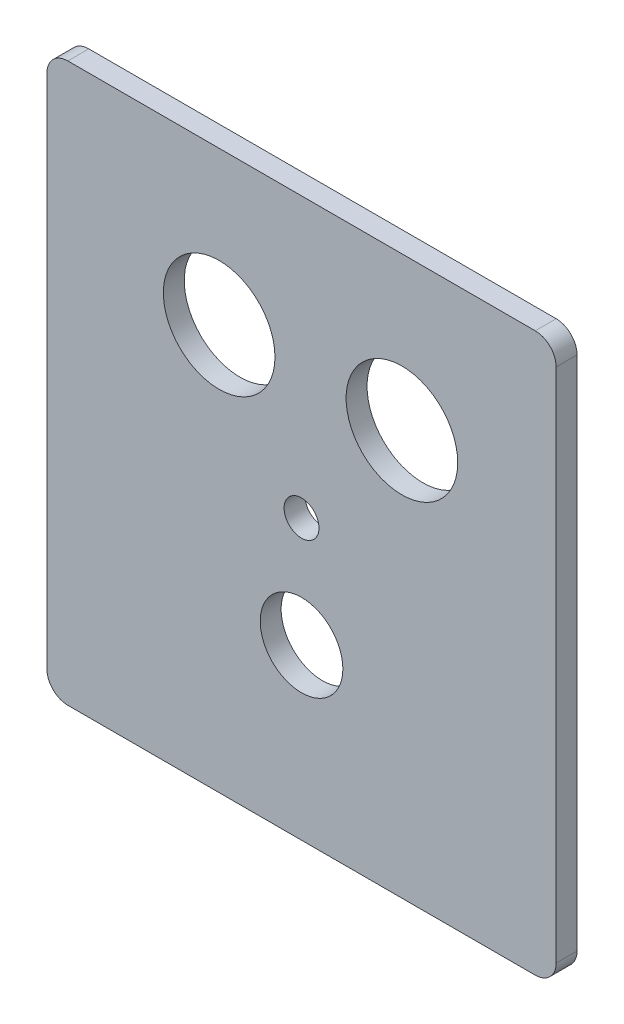
SolidWorks part; units mm, degrees
ref_plane "Front Plane" through (0, 0, 0) normal (0, 0, 1) x (1, 0, 0)
ref_plane "Top Plane" through (0, 0, 0) normal (0, 1, 0) x (1, 0, 0)
ref_plane "Right Plane" through (0, 0, 0) normal (1, 0, 0) x (0, 0, -1)
sketch "Sketch2" plane through (0, 0, 0) normal (0, 0, 1) x (1, 0, 0)
  line L1 (-105.9527, 11.6949) -> (-38.9527, 11.6949)
  line L2 (-108.9527, 8.6949) -> (-108.9527, -65.3051)
  line L3 (-105.9527, -68.3051) -> (-38.9527, -68.3051)
  line L4 (-35.9527, 8.6949) -> (-35.9527, -65.3051)
  arc A0 (-108.9527, -65.3051) -> (-105.9527, -68.3051) centre (-105.9527, -65.3051) ccw
  arc A1 (-38.9527, -68.3051) -> (-35.9527, -65.3051) centre (-38.9527, -65.3051) ccw
  arc A2 (-38.9527, 11.6949) -> (-35.9527, 8.6949) centre (-38.9527, 8.6949) cw
  arc A3 (-105.9527, 11.6949) -> (-108.9527, 8.6949) centre (-105.9527, 8.6949) ccw
  point P8 (-35.9527, -68.3051)
  point P11 (-35.9527, 11.6949)
  point P14 (-108.9527, 11.6949)
  dimension "D2" = 3
  dimension "D1" = 80
  dimension "73" = 73
extrude "Boss-Extrude2" add sketch "Sketch2" along normal blind 3
sketch "Sketch3" plane through (0, 0, 3) normal (0, 0, 1) x (1, 0, 0)
  line L0 (-108.9527, -28.3051) -> (-72.4544, -28.3051)
  line L1 (-108.9527, 8.6949) -> (-108.9527, -65.3051) construction
  line L2 (-72.4527, 11.6949) -> (-72.4527, -68.3051)
  line L3 (-38.9527, 11.6949) -> (-105.9527, 11.6949) construction
  line L4 (-105.9527, -68.3051) -> (-38.9527, -68.3051) construction
  circle A0 centre (-84.2627, -10.2334) radius 8
  circle A1 centre (-58.0627, -10.2334) radius 8
  circle A2 centre (-72.4544, -28.3051) radius 2.5
  circle A3 centre (-72.4527, -44.0755) radius 5.925
  point P17 (0, 0)
  dimension "D1" = 26.2
  dimension "D2" = 16
  dimension "D3" = 16
  dimension "D4" = 5
  dimension "D5" = 11.85
  dimension "D6" = 24.69
extrude "Cut-Extrude3" cut sketch "Sketch3" against normal blind 3
